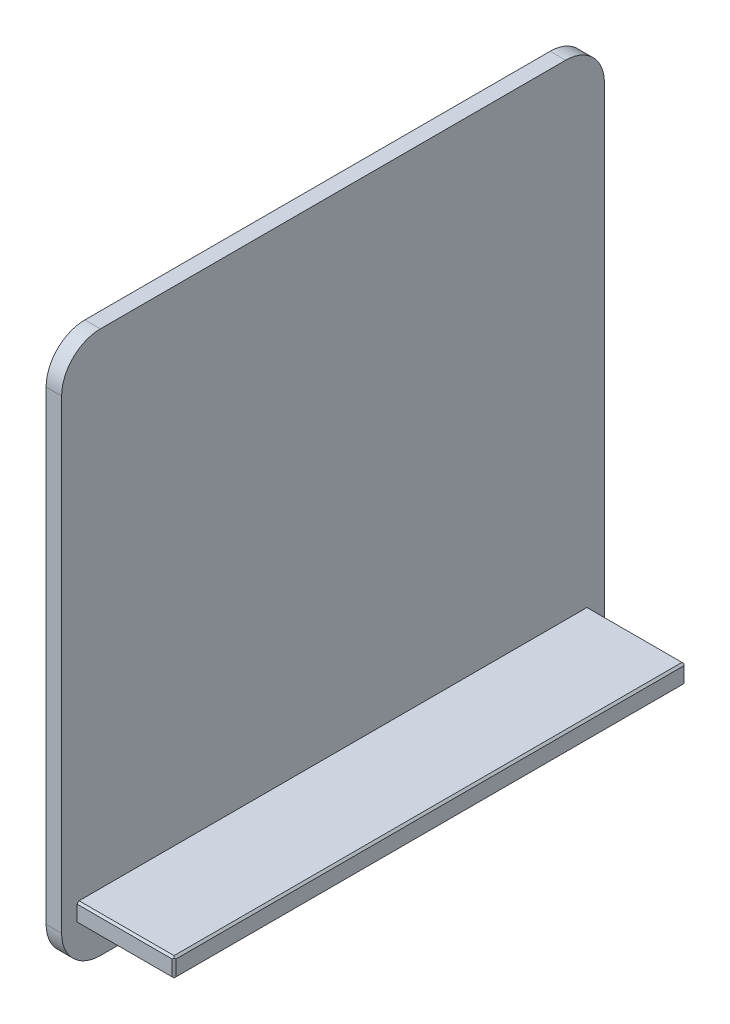
SolidWorks part; units mm, degrees
ref_plane "前视基准面" through (0, 0, 0) normal (0, 0, 1) x (1, 0, 0)
ref_plane "上视基准面" through (0, 0, 0) normal (0, 1, 0) x (1, 0, 0)
ref_plane "右视基准面" through (0, 0, 0) normal (1, 0, 0) x (0, 0, -1)
other "Configuration Table"
sketch "草图1" plane through (0, 0, 0) normal (1, 0, 0) x (0, 0, -1)
  line L1 (-70, 70) -> (70, 70)
  line L2 (-70, 70) -> (-70, -70)
  line L3 (-70, -70) -> (70, -70)
  line L4 (70, 70) -> (70, -70)
  dimension "D1" = 140
  dimension "D2" = 70
  dimension "D3" = 70
extrude "凸台-拉伸1" add sketch "草图1" along normal blind 4
sketch "草图3" plane through (4, 0, 0) normal (1, 0, 0) x (0, 0, -1)
  line L0 (-70, -70) -> (70, -70) construction
  line L1 (-66, -55) -> (66, -55)
  line L2 (-66, -55) -> (-66, -60)
  line L3 (-66, -60) -> (66, -60)
  line L4 (66, -55) -> (66, -60)
  dimension "D1" = 132
  dimension "D2" = 5
  dimension "D3" = 10
  dimension "D4" = 66
extrude "凸台-拉伸2" add sketch "草图3" along normal blind 25
chamfer "倒角1" distance 0.5 angle 45 4 edges at (29, -55, 0) (29, -57.5, -66) (29, -60, 0) (29, -57.5, 66)
chamfer "倒角2" distance 0.5 angle 45 4 edges at (16.25, -60, -66) (16.25, -55, -66) (16.25, -60, 66) (16.25, -55, 66)
fillet "圆角1" radius 10 4 edges at (2, -70, -70) (2, -70, 70) (2, 70, -70) (2, 70, 70)
